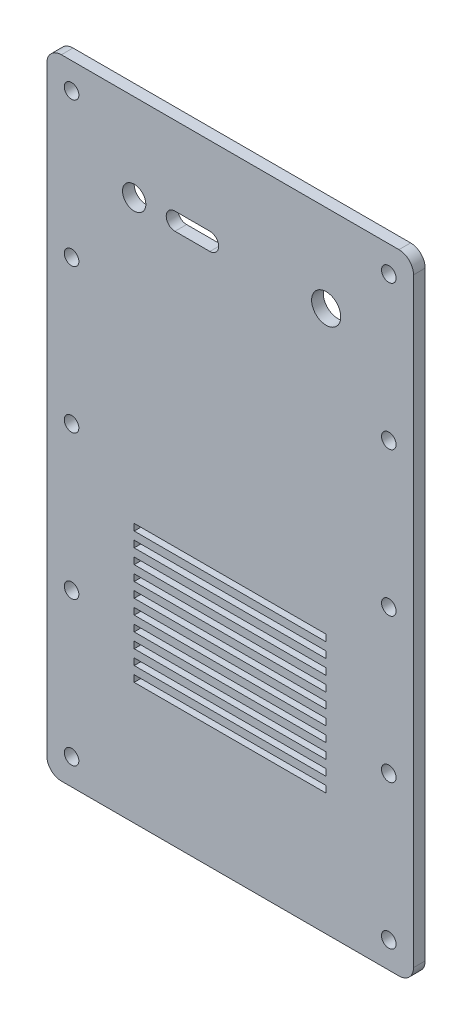
SolidWorks part; units mm, degrees
ref_plane "Front Plane" through (0, 0, 0) normal (0, 0, 1) x (1, 0, 0)
ref_plane "Top Plane" through (0, 0, 0) normal (0, 1, 0) x (1, 0, 0)
ref_plane "Right Plane" through (0, 0, 0) normal (1, 0, 0) x (0, 0, -1)
sketch "Sketch1" plane through (0, 0, 0) normal (0, 0, 1) x (1, 0, 0)
  line L1 (-22.48, -45) -> (22.48, -45) construction
  line L2 (-22.48, -45) -> (-22.48, 45) construction
  line L3 (-22.48, 45) -> (22.48, 45) construction
  line L4 (22.48, -45) -> (22.48, 45) construction
  line L5 (-22.48, -45) -> (22.48, 45) construction
  line L6 (-22.48, 45) -> (22.48, -45) construction
  line L7 (-31.48, 54) -> (31.48, 54)
  line L8 (-31.48, 54) -> (-31.48, -54)
  line L9 (-31.48, -54) -> (31.48, -54)
  line L10 (31.48, 54) -> (31.48, -54)
  line L11 (-31.48, 54) -> (31.48, -54) construction
  line L12 (-31.48, -54) -> (31.48, 54) construction
  point P0 (0, 0)
  point P6 (0, 0)
  dimension "D1" = 90
  dimension "D2" = 44.96
  dimension "D3" = 9
  dimension "D4" = 9
extrude "Boss-Extrude1" add sketch "Sketch1" along normal blind 2
fillet "Fillet1" radius 2.5 4 edges at (-31.48, -54, 1) (31.48, -54, 1) (-31.48, 54, 1) (31.48, 54, 1)
sketch "Sketch2" plane through (0, 0, 2) normal (0, 0, 1) x (1, 0, 0)
  line L0 (-22.48, -45) -> (-22.48, 45) construction
  line L1 (-27.23, -49.5) -> (27.23, -49.5) construction
  line L2 (-27.23, -49.5) -> (-27.23, 49.5) construction
  line L3 (-27.23, 49.5) -> (27.23, 49.5) construction
  line L4 (27.23, -49.5) -> (27.23, 49.5) construction
  line L5 (-27.23, -49.5) -> (27.23, 49.5) construction
  line L6 (-27.23, 49.5) -> (27.23, -49.5) construction
  circle A0 centre (-27.23, 49.5) radius 1.25
  circle A1 centre (27.23, 49.5) radius 1.25
  circle A2 centre (27.23, 24.75) radius 1.25
  circle A3 centre (27.23, 0) radius 1.25
  circle A4 centre (27.23, -24.75) radius 1.25
  circle A5 centre (27.23, -49.5) radius 1.25
  circle A6 centre (-27.23, 24.75) radius 1.25
  circle A7 centre (-27.23, 0) radius 1.25
  circle A8 centre (-27.23, -24.75) radius 1.25
  circle A9 centre (-27.23, -49.5) radius 1.25
  point P0 (0, 0)
  dimension "D3" = 2.5
  dimension "D1" = 4.75
  dimension "D2" = 99
  dimension "D4" = 5
extrude "Cut-Extrude1" cut sketch "Sketch2" against normal up to surface (2 mm away) up to face at (0, 0, 0)
sketch "Sketch3" plane through (0, 0, 2) normal (0, 0, 1) x (1, 0, 0)
  line L0 (-9.48, 39) -> (-3.48, 39) construction
  line L1 (-9.48, 40.5) -> (-3.48, 40.5)
  line L2 (-9.48, 37.5) -> (-3.48, 37.5)
  line L3 (28.98, 54) -> (-28.98, 54) construction
  line L4 (-31.48, 51.5) -> (-31.48, -51.5) construction
  line L5 (31.48, -51.5) -> (31.48, 51.5) construction
  line L6 (-16.48, -13.0694) -> (-16.48, -11.9306)
  line L7 (-16.48, -10.5694) -> (16.48, -10.5694)
  line L8 (-16.48, -10.5694) -> (-16.48, -9.4306)
  line L9 (-16.48, -9.4306) -> (16.48, -9.4306)
  line L10 (16.48, -10.5694) -> (16.48, -9.4306)
  line L11 (-16.48, -10.5694) -> (16.48, -9.4306) construction
  line L12 (-16.48, -9.4306) -> (16.48, -10.5694) construction
  line L13 (-16.48, -13.0694) -> (16.48, -13.0694)
  line L14 (16.48, -13.0694) -> (16.48, -11.9306)
  line L15 (-16.48, -11.9306) -> (16.48, -11.9306)
  line L16 (-16.48, -15.5694) -> (-16.48, -14.4306)
  line L17 (-16.48, -15.5694) -> (16.48, -15.5694)
  line L18 (16.48, -15.5694) -> (16.48, -14.4306)
  line L19 (-16.48, -14.4306) -> (16.48, -14.4306)
  line L20 (-16.48, -18.0694) -> (-16.48, -16.9306)
  line L21 (-16.48, -18.0694) -> (16.48, -18.0694)
  line L22 (16.48, -18.0694) -> (16.48, -16.9306)
  line L23 (-16.48, -16.9306) -> (16.48, -16.9306)
  line L24 (-16.48, -20.5694) -> (-16.48, -19.4306)
  line L25 (-16.48, -20.5694) -> (16.48, -20.5694)
  line L26 (16.48, -20.5694) -> (16.48, -19.4306)
  line L27 (-16.48, -19.4306) -> (16.48, -19.4306)
  line L28 (-16.48, -23.0694) -> (-16.48, -21.9306)
  line L29 (-16.48, -23.0694) -> (16.48, -23.0694)
  line L30 (16.48, -23.0694) -> (16.48, -21.9306)
  line L31 (-16.48, -21.9306) -> (16.48, -21.9306)
  line L32 (-16.48, -25.5694) -> (-16.48, -24.4306)
  line L33 (-16.48, -25.5694) -> (16.48, -25.5694)
  line L34 (16.48, -25.5694) -> (16.48, -24.4306)
  line L35 (-16.48, -24.4306) -> (16.48, -24.4306)
  line L36 (-16.48, -28.0694) -> (-16.48, -26.9306)
  line L37 (-16.48, -28.0694) -> (16.48, -28.0694)
  line L38 (16.48, -28.0694) -> (16.48, -26.9306)
  line L39 (-16.48, -26.9306) -> (16.48, -26.9306)
  line L40 (-16.48, -30.5694) -> (-16.48, -29.4306)
  line L41 (-16.48, -30.5694) -> (16.48, -30.5694)
  line L42 (16.48, -30.5694) -> (16.48, -29.4306)
  line L43 (-16.48, -29.4306) -> (16.48, -29.4306)
  line L44 (-16.48, -33.0694) -> (-16.48, -31.9306)
  line L45 (-16.48, -33.0694) -> (16.48, -33.0694)
  line L46 (16.48, -33.0694) -> (16.48, -31.9306)
  line L47 (-16.48, -31.9306) -> (16.48, -31.9306)
  circle A0 centre (16.48, 39) radius 2.5
  circle A1 centre (-16.48, 39) radius 2
  arc A2 (-9.48, 40.5) -> (-9.48, 37.5) centre (-9.48, 39) ccw
  arc A3 (-3.48, 37.5) -> (-3.48, 40.5) centre (-3.48, 39) ccw
  point P6 (-6.48, 39)
  point P11 (-6.48, 37.5)
  point P21 (0, -10)
  dimension "D1" = 5
  dimension "D2" = 4
  dimension "D3" = 6
  dimension "D4" = 3
  dimension "D5" = 15
  dimension "D6" = 15
  dimension "D7" = 10
  dimension "D8" = 15
  dimension "D9" = 1.1389
  dimension "D10" = 15
  dimension "D11" = 10
  dimension "D13" = 2.5
  dimension "D12" = 10
extrude "Cut-Extrude2" cut sketch "Sketch3" against normal up to surface (2 mm away) up to face at (28.48, -49.5, 0)
equation "\"case_width\"=44.96"
equation "\"D2@Sketch1\"=\"case_width\""
